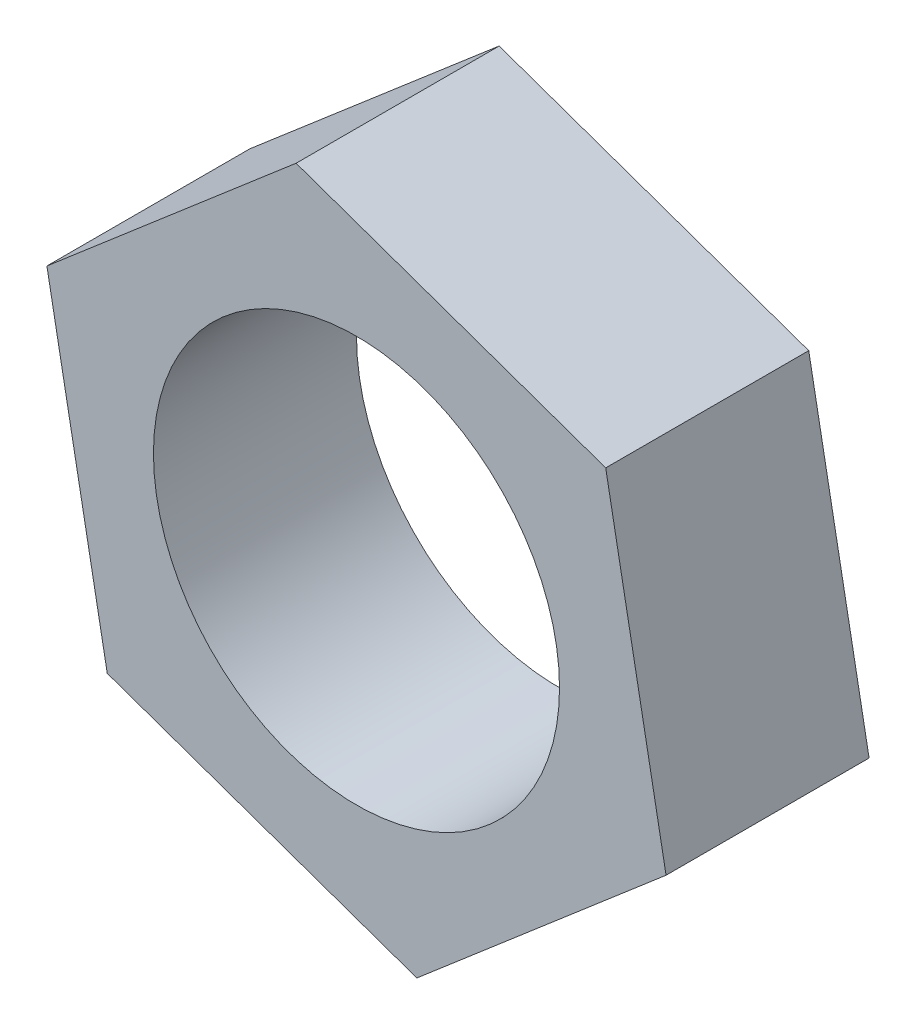
SolidWorks part; units mm, degrees
material "AISI 304"
ref_plane "Front Plane" through (0, 0, 0) normal (0, 0, 1) x (1, 0, 0)
ref_plane "Top Plane" through (0, 0, 0) normal (0, 1, 0) x (1, 0, 0)
ref_plane "Right Plane" through (0, 0, 0) normal (1, 0, 0) x (0, 0, -1)
sketch "Sketch1" plane through (0, 0, 0) normal (0, 0, 1) x (1, 0, 0)
  line L1 (1.4864, -7.9451) -> (7.6238, -2.6852)
  line L2 (7.6238, -2.6852) -> (6.1374, 5.2598)
  line L3 (6.1374, 5.2598) -> (-1.4864, 7.9451)
  line L4 (-1.4864, 7.9451) -> (-7.6238, 2.6852)
  line L5 (-7.6238, 2.6852) -> (-6.1374, -5.2598)
  line L6 (-6.1374, -5.2598) -> (1.4864, -7.9451)
  circle A0 centre (0, 0) radius 7 construction
  circle A1 centre (0, 0) radius 5
  dimension "D1" = 14
  dimension "D3" = 10
  dimension "D2" = 16.1658
extrude "Boss-Extrude1" add sketch "Sketch1" along normal mid plane 5
